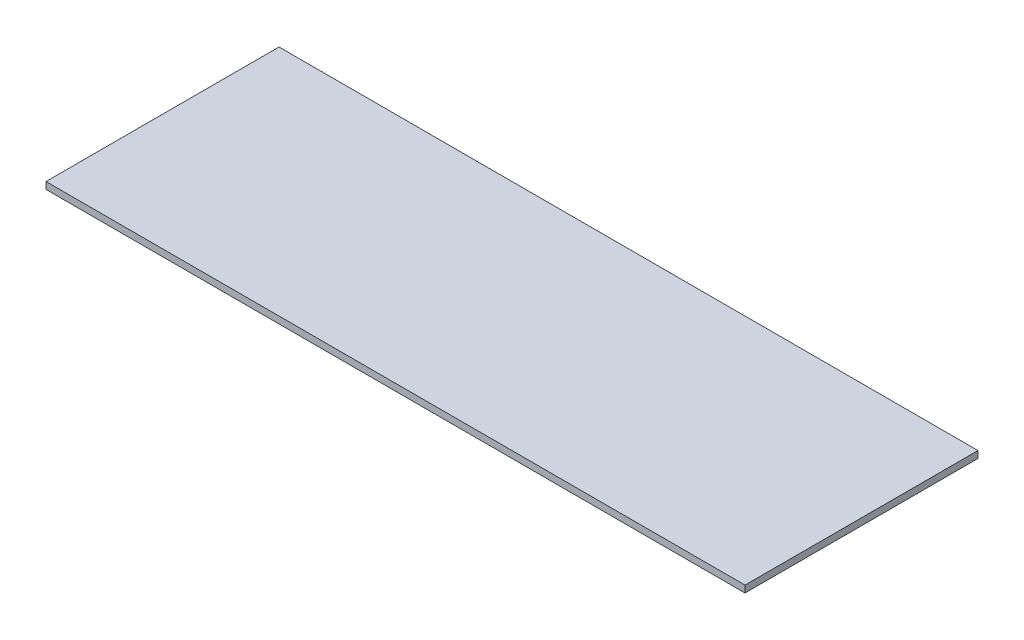
SolidWorks part; units mm, degrees
ref_plane "Front Plane" through (0, 0, 0) normal (0, 0, 1) x (1, 0, 0)
ref_plane "Top Plane" through (0, 0, 0) normal (0, 1, 0) x (1, 0, 0)
ref_plane "Right Plane" through (0, 0, 0) normal (1, 0, 0) x (0, 0, -1)
sketch "Sketch1" plane through (0, 0, 0) normal (0, 1, 0) x (1, 0, 0)
  line L1 (304.8, -101.6) -> (-304.8, -101.6)
  line L2 (304.8, -101.6) -> (304.8, 101.6)
  line L3 (304.8, 101.6) -> (-304.8, 101.6)
  line L4 (-304.8, -101.6) -> (-304.8, 101.6)
  line L5 (304.8, -101.6) -> (-304.8, 101.6) construction
  line L6 (304.8, 101.6) -> (-304.8, -101.6) construction
  point P0 (0, 0)
  dimension "D1" = 609.6
  dimension "D2" = 203.2
extrude "Boss-Extrude1" add sketch "Sketch1" along normal blind 6
